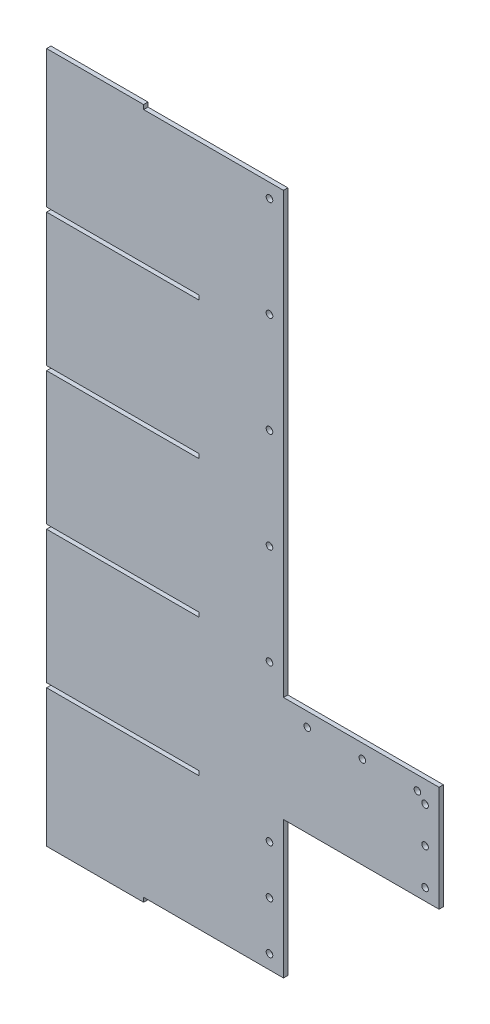
SolidWorks part; units mm, degrees
material "6061-T6 (SS)"
ref_plane "X-Y Datum" through (0, 0, 0) normal (0, 0, 1) x (1, 0, 0)
ref_plane "X-Z Datum" through (0, 0, 0) normal (0, 1, 0) x (1, 0, 0)
ref_plane "Y-Z Datum" through (0, 0, 0) normal (1, 0, 0) x (0, 0, -1)
sketch "Sketch1" plane through (0, 0, 0) normal (0, 0, 1) x (1, 0, 0)
  line L1 (129.0131, 254.2454) -> (-18.6854, 254.2454)
  line L3 (129.0131, -241.3467) -> (-18.6854, -241.3467)
  line L4 (-18.6854, 254.2454) -> (-18.6854, 157.667)
  line L24 (129.0131, 254.2454) -> (129.0131, -241.3467)
  line L25 (92.0885, 157.667) -> (-18.6854, 157.667)
  line L27 (92.0885, 154.492) -> (-18.6854, 154.492)
  line L29 (92.0885, 57.9136) -> (-18.6854, 57.9136)
  line L31 (92.0885, 54.7386) -> (-18.6854, 54.7386)
  line L33 (92.0885, -41.8399) -> (-18.6854, -41.8399)
  line L35 (92.0885, -45.0149) -> (-18.6854, -45.0149)
  line L37 (92.0885, -141.5933) -> (-18.6854, -141.5933)
  line L39 (92.0885, -144.7683) -> (-18.6854, -144.7683)
  line L41 (92.0885, -141.5933) -> (92.0885, -144.7683)
  line L42 (92.0885, -41.8399) -> (92.0885, -45.0149)
  line L43 (92.0885, 57.9136) -> (92.0885, 54.7386)
  line L44 (-18.6854, -144.7683) -> (-18.6854, -241.3467)
  line L45 (-18.6854, -45.0149) -> (-18.6854, -141.5933)
  line L46 (-18.6854, 54.7386) -> (-18.6854, -41.8399)
  line L47 (-18.6854, 154.492) -> (-18.6854, 57.9136)
  line L48 (92.0885, 157.667) -> (92.0885, 154.492)
extrude "Boss-Extrude2" add sketch "Sketch1" along normal blind 3.175
sketch "Sketch2" plane through (0, 0, 3.175) normal (0, 0, 1) x (1, 0, 0)
  line L0 (129.0131, -241.3467) -> (153.4072, -227.2627) construction
  line L2 (129.0131, 254.2454) -> (129.0131, -241.3467)
  line L15 (153.4072, -227.2627) -> (153.4072, -187.8927)
  line L18 (153.4072, -143.1808) -> (153.4072, 240.1614)
  line L19 (153.4072, 240.1614) -> (153.4072, 254.2454)
  line L21 (153.4072, -187.8927) -> (153.4072, -143.1808)
  line L22 (153.4072, 254.2454) -> (129.0131, 254.2454)
  line L23 (129.0131, -241.3467) -> (153.4072, -241.3467)
  line L24 (153.4072, -241.3467) -> (153.4072, -227.2627)
extrude "Boss-Extrude3" add sketch "Sketch2" against normal through all
sketch "Sketch3" plane through (0, 0, 3.175) normal (0, 0, 1) x (1, 0, 0)
  line L8 (153.4072, 6.4494) -> (-81.8872, 6.4494) construction
  line L9 (51.8072, 257.4204) -> (51.8072, 254.2454)
  line L18 (153.4072, 257.4204) -> (51.8072, 257.4204)
  line L19 (153.4072, 257.4204) -> (153.4072, 270.1204)
  line L20 (153.4072, 270.1204) -> (30.4963, 270.1204)
  line L21 (30.4963, 270.1204) -> (6.7146, 286.3764)
  line L22 (-18.6854, 286.3764) -> (6.7146, 286.3764)
  line L23 (-18.6854, 254.2454) -> (-18.6854, 286.3764)
  line L24 (51.8072, 254.2454) -> (-18.6854, 254.2454)
extrude "Boss-Extrude4" [suppressed] add sketch "Sketch3" against normal through all
sketch "Sketch4" [suppressed] plane through (0, 0, 3.175) normal (0, 0, 1) x (1, 0, 0)
  line L1 (153.4072, 270.1204) -> (221.7231, 270.1204)
  line L2 (153.4072, 270.1204) -> (153.4072, 257.4204)
  line L3 (153.4072, 257.4204) -> (221.7231, 257.4204)
  line L4 (221.7231, 270.1204) -> (221.7231, 257.4204)
  line L5 (153.4072, 254.2454) -> (221.7231, 254.2454)
  line L6 (153.4072, 254.2454) -> (153.4072, 157.667)
  line L7 (153.4072, 157.667) -> (221.7231, 157.667)
  line L8 (221.7231, 254.2454) -> (221.7231, 157.667)
  dimension "D1" = 68.3158
extrude "Boss-Extrude5" [suppressed] add sketch "Sketch4" against normal through all
sketch "Sketch7" plane through (0, 0, 3.175) normal (0, 0, 1) x (1, 0, 0)
  line L0 (92.0885, -141.5933) -> (202.7766, -141.5933) construction
  line L1 (153.2294, -141.5933) -> (153.4072, -64.8271)
  line L2 (153.4072, -241.3467) -> (153.4072, 254.2454) construction
  line L3 (153.4072, -64.8271) -> (266.4372, -64.8271)
  line L4 (266.4372, -64.8271) -> (266.4372, -141.5933)
  line L5 (266.4372, -141.5933) -> (153.2294, -141.5933)
extrude "Boss-Extrude6" add sketch "Sketch7" against normal through all
sketch "Sketch8" plane through (0, 0, 3.175) normal (0, 0, 1) x (1, 0, 0)
  line L1 (-18.6854, 254.2454) -> (51.8072, 254.2454)
  line L2 (-18.6854, 254.2454) -> (-18.6854, 257.4204)
  line L3 (-18.6854, 257.4204) -> (51.8072, 257.4204)
  line L4 (51.8072, 254.2454) -> (51.8072, 257.4204)
  line L5 (-18.6854, -241.3467) -> (51.8072, -241.3467)
  line L6 (-18.6854, -241.3467) -> (-18.6854, -244.5217)
  line L7 (-18.6854, -244.5217) -> (51.8072, -244.5217)
  line L8 (51.8072, -241.3467) -> (51.8072, -244.5217)
extrude "Boss-Extrude7" add sketch "Sketch8" against normal through all
sketch "Sketch12" plane through (0, 0, 3.175) normal (0, 0, 1) x (1, 0, 0)
  line L0 (-18.6854, 257.4204) -> (289.5814, 257.4204) construction
  line L1 (-18.6854, 257.4204) -> (-18.6854, -144.2662) construction
  line L2 (-18.6854, -144.2662) -> (289.5814, -144.2662) construction
  line L3 (289.5814, 257.4204) -> (289.5814, -144.2662) construction
  point P0 (143.2472, 244.0133)
  point P1 (143.2472, 171.1213)
  point P2 (143.2472, 98.2292)
  point P3 (143.2472, 25.3372)
  point P4 (143.2472, -47.5549)
  point P5 (170.6792, -74.9869)
  point P6 (210.7117, -74.9869)
  point P7 (250.7441, -74.9869)
  point P8 (256.2772, -80.52)
  point P9 (256.2772, -106.7475)
  point P10 (256.2772, -132.9751)
  point P15 (143.2472, -160.6738)
  point P16 (143.2472, -195.8942)
  point P17 (143.2472, -231.1146)
hole_wizard "M4 Clearance Hole2" positions "Sketch13" profile "Sketch14" hole size "M4" standard "ANSI Metric" end condition through all
sketch "Sketch13" plane through (0, 0, 3.175) normal (0, 0, 1) x (1, 0, 0)
  point P0 (143.2472, 244.0133)
  point P3 (143.2472, 171.1213)
  point P6 (143.2472, 98.2292)
  point P9 (143.2472, 25.3372)
  point P12 (143.2472, -47.5549)
  point P15 (170.6792, -74.9869)
  point P18 (210.7117, -74.9869)
  point P21 (250.7441, -74.9869)
  point P24 (256.2772, -80.52)
  point P27 (256.2772, -106.7475)
  point P30 (256.2772, -132.9751)
  point P33 (143.2472, -160.6738)
  point P36 (143.2472, -195.8942)
  point P39 (143.2472, -231.1146)
sketch "Sketch14" plane through (143.2472, 244.0133, 3.175) normal (1, 0, 0) x (0, -1, 0)
  line L0 (0, 0) -> (0, 3.175)
  line L1 (0, 3.175) -> (2.4, 3.175)
  line L2 (2.4, 3.175) -> (2.4, 0)
  line L5 (2.4, 0) -> (0, 0)
  line L11 (0, -6.35) -> (0, 107.95) construction
  dimension "Thru Hole Dia." = 4.8
  dimension "Thru Hole Depth" = 3.175
